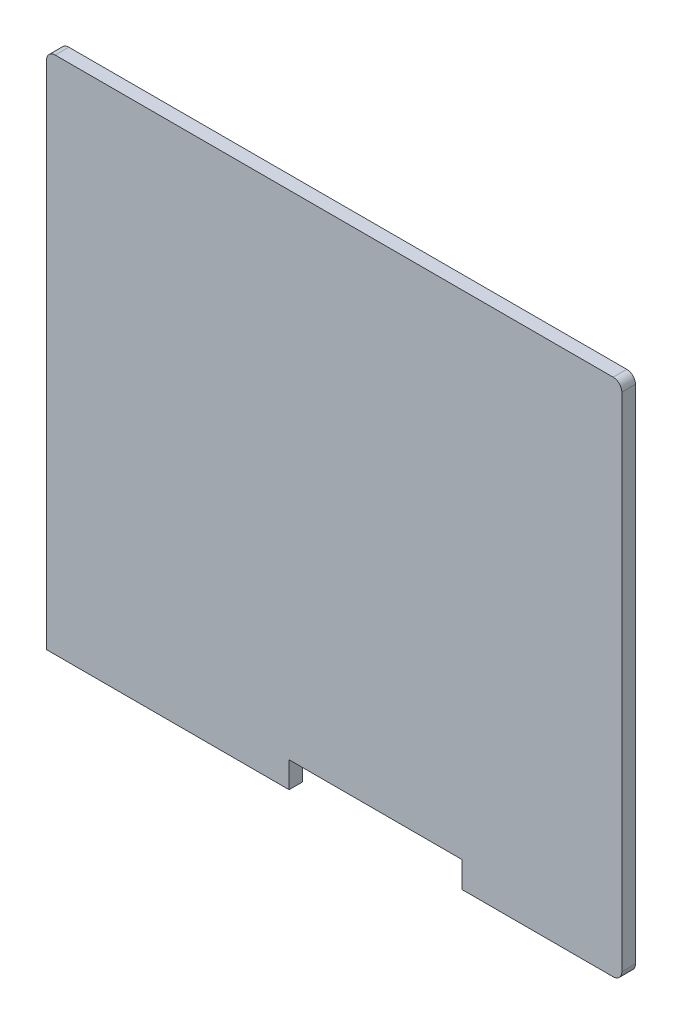
SolidWorks part; units mm, degrees
ref_plane "Front Plane" through (0, 0, 0) normal (0, 0, 1) x (1, 0, 0)
ref_plane "Top Plane" through (0, 0, 0) normal (0, 1, 0) x (1, 0, 0)
ref_plane "Right Plane" through (0, 0, 0) normal (1, 0, 0) x (0, 0, -1)
sketch "BPR2 PCB Outline" plane through (0, 0, 0) normal (0, 0, 1) x (1, 0, 0)
  line L0 (83.597, 7.3176) -> (83.597, 10.3176)
  line L1 (56.571, 67.3176) -> (121.041, 67.3176)
  line L2 (55.571, 66.3176) -> (55.571, 7.3176)
  line L3 (55.571, 7.3176) -> (83.597, 7.3176)
  line L4 (122.041, 66.3176) -> (122.041, 8.3176)
  line L5 (83.597, 10.3176) -> (103.597, 10.3176)
  line L6 (103.597, 10.3176) -> (103.597, 7.3176)
  line L7 (103.597, 7.3176) -> (121.041, 7.3176)
  arc A0 (121.041, 7.3176) -> (122.041, 8.3176) centre (121.041, 8.3176) ccw
  arc A1 (121.041, 67.3176) -> (122.041, 66.3176) centre (121.041, 66.3176) cw
  arc A2 (56.571, 67.3176) -> (55.571, 66.3176) centre (56.571, 66.3176) ccw
  point P6 (122.041, 7.3176)
  point P9 (122.041, 67.3176)
  point P12 (55.571, 67.3176)
  dimension "D2" = 66.47
  dimension "D4" = 17.444
  dimension "D3" = 1
  dimension "D1" = 60
  dimension "D5" = 20
  dimension "D6" = 3
sketch "23" plane through (0, 0, 0) normal (0, 0, 1) x (1, 0, 0)
  point P0 (0, 0)
extrude "Boss-Extrude1" add sketch "BPR2 PCB Outline" against normal blind 1.5748
